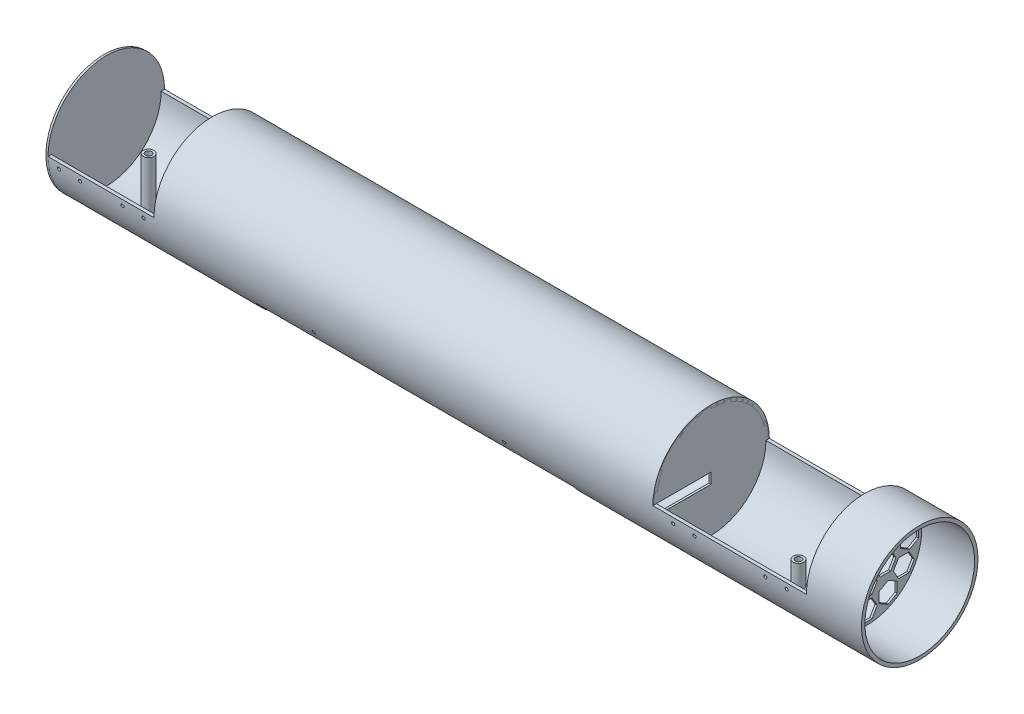
SolidWorks part; units mm, degrees
other "标注1"
sketch "草图27" plane through (-2, 77.9653, 55) normal (0, 1, 0) x (-1, 0, 0)
ref_plane "前视基准面" through (0, 0, 0) normal (0, 0, 1) x (1, 0, 0)
ref_plane "上视基准面" through (0, 0, 0) normal (0, 1, 0) x (1, 0, 0)
ref_plane "右视基准面" through (0, 0, 0) normal (1, 0, 0) x (0, 0, -1)
sketch "草图2" plane through (0, 0, 0) normal (1, 0, 0) x (0, 0, -1)
  circle A0 centre (0, 0) radius 55
  circle A1 centre (0, 0) radius 51.8
  dimension "D1" = 110
  dimension "D2" = 103.6
extrude "凸台-拉伸1" add sketch "草图2" along normal blind 768
ref_plane "基准面4" through (100, 0, 0) normal (1, 0, 0) x (0, 0, -1)
sketch "草图3" plane through (100, 0, 0) normal (1, 0, 0) x (0, 0, -1)
  circle A0 centre (0, 0) radius 54
  dimension "D1" = 108
extrude "凸台-拉伸2" add sketch "草图3" along normal blind 2 separate body
ref_plane "基准面5" through (400, 0, 0) normal (1, 0, 0) x (0, 0, -1)
ref_plane "基准面6" through (565, 0, 0) normal (1, 0, 0) x (0, 0, -1)
sketch "草图7" plane through (0, 0, 0) normal (1, 0, 0) x (0, 0, -1)
  circle A1 centre (0, 0) radius 55
extrude "凸台-拉伸5" add sketch "草图7" against normal blind 2 separate body
ref_plane "基准面7" through (102, 0, 0) normal (1, 0, 0) x (0, 0, -1)
ref_plane "基准面8" through (450, 0, 0) normal (1, 0, 0) x (0, 0, -1)
sketch "草图8" plane through (450, 0, 0) normal (1, 0, 0) x (0, 0, -1)
  circle A0 centre (0, 0) radius 53
ref_plane "基准面9" through (507.5, 0, 0) normal (1, 0, 0) x (0, 0, -1)
ref_plane "基准面10" through (615, 0, 0) normal (1, 0, 0) x (0, 0, -1)
sketch "草图9" plane through (615, 0, 0) normal (1, 0, 0) x (0, 0, -1)
  circle A0 centre (0, 0) radius 53
sketch "草图12" plane through (0, 0, 0) normal (0, 0, 1) x (1, 0, 0)
  line L0 (615, 0) -> (565, 0)
  line L1 (615, -60.5) -> (615, 60.5) construction
  line L2 (768, 0) -> (0, 0) construction
  line L3 (565, -60.5) -> (565, 60.5) construction
sketch "草图14" plane through (0, 0, 0) normal (0, 1, 0) x (1, 0, 0)
  line L1 (571, 55) -> (716, 55)
  line L3 (571, 0) -> (716, 0)
  line L4 (716, 55) -> (716, 0)
  line L5 (768, -55) -> (768, 55) construction
  line L9 (571, 55) -> (571, 0)
  dimension "D1" = 52
  dimension "D3" = 145
ref_plane "基准面11" through (617, 0, 0) normal (1, 0, 0) x (0, 0, -1)
sketch "草图15" plane through (617, 0, 0) normal (1, 0, 0) x (0, 0, -1)
  circle A0 centre (0, 0) radius 53
revolve "切除-旋转1" cut sketch "草图14" angle 180 about L3
sketch "草图16" plane through (0, 0, 0) normal (0, 1, 0) x (1, 0, 0)
  line L0 (100, -60.5) -> (100, 60.5) construction
  line L1 (0, 0) -> (100, 0)
  line L2 (0, 0) -> (0, 55)
  line L3 (0, 55) -> (100, 55)
  line L4 (100, 0) -> (100, 55)
  line L5 (571, 55) -> (0, 55) construction
  dimension "D1" = 100
  dimension "D2" = 55
revolve "切除-旋转2" cut sketch "草图16" angle 180 about L1
ref_plane "基准面12" through (435, 0, 0) normal (1, 0, 0) x (0, 0, -1)
sketch "草图17" plane through (435, 0, 0) normal (1, 0, 0) x (0, 0, -1)
  line L0 (0, 77.9653) -> (0, -80.6413) construction
  circle A0 centre (0, -67) radius 12
  circle A1 centre (0, -67) radius 10
  circle A2 centre (0, 0) radius 55 construction
  dimension "D1" = 24
  dimension "D2" = 20
ref_plane "基准面13" through (200, 0, 0) normal (1, 0, 0) x (0, 0, -1)
ref_plane "基准面14" through (0, 0, -50) normal (0, 0, 1) x (1, 0, 0)
sketch "草图19" plane through (0, 0, -50) normal (0, 0, 1) x (1, 0, 0)
  line L0 (716, 0) -> (571, 0) construction
  line L1 (716, 55) -> (716, 0) construction
  line L2 (571, 0) -> (571, 51.8) construction
  circle A0 centre (693, -5.4) radius 1.5
  circle A1 centre (673, -5.4) radius 1.5
  circle A2 centre (614, -5.4) radius 1.5
  circle A3 centre (594, -5.4) radius 1.5
  dimension "D1" = 3
  dimension "D2" = 3
  dimension "D6" = 3
  dimension "D7" = 3
  dimension "D3" = 20
  dimension "D4" = 5.4
  dimension "D5" = 23
  dimension "D8" = 20
  dimension "D9" = 5.4
  dimension "D10" = 23
  dimension "D11" = 5.4
sketch "草图22" plane through (0, 0, -50) normal (0, 0, 1) x (1, 0, 0)
  line L0 (0, 0) -> (0, -55) construction
  line L1 (100, 55) -> (100, 0) construction
  line L2 (100, 0) -> (0, 0) construction
  circle A0 centre (10, -5.4) radius 1.5
  circle A1 centre (30, -5.4) radius 1.5
  circle A2 centre (70, -5.4) radius 1.5
  circle A3 centre (90, -5.4) radius 1.5
  dimension "D1" = 3
  dimension "D2" = 3
  dimension "D7" = 3
  dimension "D8" = 3
  dimension "D3" = 10
  dimension "D4" = 20
  dimension "D5" = 20
  dimension "D6" = 10
  dimension "D9" = 5.4
extrude "切除-拉伸4" cut sketch "草图22" along normal through all
ref_plane "基准面16" through (597, 0, 0) normal (1, 0, 0) x (0, 0, -1)
sketch "草图23" plane through (597, 0, 0) normal (1, 0, 0) x (0, 0, -1)
  circle A0 centre (0, 0) radius 53
sketch "草图24" plane through (0, 0, -50) normal (0, 0, 1) x (1, 0, 0)
  line L0 (716, 0) -> (571, 0) construction
  line L1 (571, 0) -> (571, 55) construction
  line L2 (716, 55) -> (716, 0) construction
  circle A0 centre (590, -5.4) radius 1.5
  circle A1 centre (610, -5.4) radius 1.5
  circle A2 centre (677, -5.4) radius 1.5
  circle A3 centre (697, -5.4) radius 1.5
  dimension "D3" = 3
  dimension "D4" = 3
  dimension "D6" = 3
  dimension "D7" = 3
  dimension "D1" = 20
  dimension "D2" = 5.4
  dimension "D5" = 20
  dimension "D8" = 5.4
  dimension "D9" = 19
  dimension "D10" = 19
extrude "切除-拉伸5" cut sketch "草图24" along normal through all
ref_plane "基准面17" through (222.4934, 0, 0) normal (1, 0, 0) x (0, 0, -1)
sketch "草图25" plane through (222.4934, 0, 0) normal (1, 0, 0) x (0, 0, -1)
  circle A0 centre (0, -67) radius 12
  circle A1 centre (0, -67) radius 10
  circle A2 centre (0, 0) radius 55 construction
  dimension "D1" = 24
  dimension "D2" = 20
ref_plane "基准面18" through (0, 0, 0) normal (1, 0, 0) x (0, 0, -1)
ref_plane "基准面19" through (470, 0, 0) normal (1, 0, 0) x (0, 0, -1)
ref_plane "基准面20" through (718, 0, 0) normal (1, 0, 0) x (0, 0, -1)
sketch "草图28" plane through (718, 0, 0) normal (1, 0, 0) x (0, 0, -1)
  circle A0 centre (0, 0) radius 54
  dimension "D1" = 108
extrude "凸台-拉伸16" add sketch "草图28" against normal blind 2 separate body
ref_plane "基准面21" through (571, 0, 0) normal (1, 0, 0) x (0, 0, -1)
sketch "草图29" plane through (571, 0, 0) normal (1, 0, 0) x (0, 0, -1)
  circle A0 centre (0, 0) radius 54
  dimension "D1" = 108
extrude "凸台-拉伸17" add sketch "草图29" against normal blind 2 separate body
sketch "草图30" plane through (0, 0, 0) normal (0, 0, 1) x (1, 0, 0)
  line L3 (185.5, 0) -> (485.5, 0)
  line L6 (0, -55) -> (768, -55) construction
  line L7 (185.5, 0) -> (485.5, 0)
  line L8 (185.5, 0) -> (185.5, -55)
  line L9 (185.5, -55) -> (485.5, -55)
  line L10 (485.5, 0) -> (485.5, -55)
  line L11 (571, 0) -> (571, 55) construction
  dimension "D1" = 300
  dimension "D2" = 55
  dimension "D3" = 85.5
sketch "草图31" plane through (571, 0, 0) normal (1, 0, 0) x (0, 0, -1)
  line L0 (-52.8334, 0) -> (0, 0)
  line L1 (0, 0) -> (0, -10)
  line L2 (0, -10) -> (-51.8784, -10)
  arc A0 (-52.8334, 0) -> (-51.8784, -10) centre (0, 0) ccw
  dimension "D1" = 10
extrude "切除-拉伸6" cut sketch "草图31" against normal blind 536
sketch "草图32" plane through (0, 0, 0) normal (0, 0, 1) x (1, 0, 0)
  line L0 (0, -55) -> (768, -55) construction
  line L1 (185.5, 0) -> (485.5, 0)
  line L2 (185.5, 0) -> (185.5, -55)
  line L3 (185.5, -55) -> (485.5, -55)
  line L4 (485.5, 0) -> (485.5, -55)
  line L5 (100, 55) -> (100, 0) construction
  dimension "D1" = 300
  dimension "D2" = 55
  dimension "D3" = 85.5
revolve "切除-旋转4" cut sketch "草图32" angle 54 about axis through (768, 0, 0) along (-1, 0, 0) other way angle 54
sketch "草图35" plane through (718, 0, 0) normal (1, 0, 0) x (0, 0, -1)
  line L0 (0, 0) -> (-43.6869, -31.7404)
  line L1 (0, 0) -> (43.6869, -31.7404)
  line L2 (0, 0) -> (0, -54) construction
  circle A0 centre (0, 0) radius 54 construction
  arc A1 (-43.6869, -31.7404) -> (43.6869, -31.7404) centre (0, 0) ccw
  dimension "D1" = 108
ref_plane "基准面22" through (0, 0, 45) normal (0, 0, 1) x (1, 0, 0)
sketch "草图36" plane through (0, 0, 45) normal (0, 0, 1) x (1, 0, 0)
  line L0 (185.5, -32.3282) -> (485.5, -32.3282) construction
  line L1 (485.5, -32.3282) -> (485.5, -55) construction
  line L2 (185.5, -55) -> (185.5, -32.3282) construction
  circle A0 centre (425.5, -23.4722) radius 1.5
  circle A1 centre (245.5, -23.4722) radius 1.5
  dimension "D3" = 3
  dimension "D5" = 3
  dimension "D1" = 8.856
  dimension "D2" = 60
  dimension "D4" = 60
extrude "切除-拉伸7" cut sketch "草图36" against normal through all both and the other way through all
sketch "草图37" plane through (0, 0, 0) normal (0, 1, 0) x (1, 0, 0)
  line L1 (0, -55) -> (0, 55) construction
  circle A0 centre (40, 0) radius 5
  circle A1 centre (40, 0) radius 3
  dimension "D1" = 10
  dimension "D2" = 6
  dimension "D3" = 40
extrude "凸台-拉伸19" add sketch "草图37" against normal up to body
sketch "草图39" plane through (0, 0, 0) normal (0, 1, 0) x (1, 0, 0)
  line L1 (716, 51.8) -> (716, -51.8) construction
  line L2 (716, 55) -> (716, -55) construction
  circle A0 centre (653.5, 0) radius 5
  circle A1 centre (653.5, 0) radius 3
  point P9 (716, 0)
  dimension "D1" = 10
  dimension "D2" = 6
  dimension "D3" = 62.5
extrude "凸台-拉伸21" add sketch "草图39" against normal up to body
sketch "草图40" plane through (0, 0, 0) normal (0, 1, 0) x (1, 0, 0)
  circle A0 centre (40, 0) radius 3 construction
  circle A1 centre (40, 0) radius 5
  circle A2 centre (40, 0) radius 5
  circle A3 centre (40, 0) radius 3
  dimension "D1" = 0
extrude "切除-拉伸8" cut sketch "草图40" against normal blind 5
sketch "草图41" plane through (0, 0, 0) normal (0, 1, 0) x (1, 0, 0)
  circle A1 centre (653.5, 0) radius 3 construction
  circle A2 centre (653.5, 0) radius 5
  circle A3 centre (653.5, 0) radius 5
  circle A4 centre (653.5, 0) radius 3
  dimension "D1" = 0
extrude "切除-拉伸9" cut sketch "草图41" against normal blind 30
ref_plane "基准面23" through (0, 0, -52.0375) normal (0, 0, 1) x (1, 0, 0)
sketch "草图42" plane through (0, 0, -52.0375) normal (0, 0, 1) x (1, 0, 0)
  line L0 (716, 0) -> (571, 0) construction
  line L1 (716, 55) -> (716, 0) construction
  circle A0 centre (711, -5) radius 1.5
  dimension "D1" = 3
  dimension "D2" = 5
  dimension "D3" = 5
extrude "切除-拉伸10" cut sketch "草图42" against normal blind 44
sketch "草图44" plane through (718, 0, 0) normal (1, 0, 0) x (0, 0, -1)
  line L0 (0, 40.3627) -> (0, 0) construction
  line L1 (4.9412, 48.8975) -> (-4.9208, 48.9093)
  line L2 (-4.9208, 48.9093) -> (-9.8619, 40.3745)
  line L3 (-9.8619, 40.3745) -> (-4.9412, 31.8279)
  line L4 (-4.9412, 31.8279) -> (4.9208, 31.8161)
  line L5 (4.9208, 31.8161) -> (9.8619, 40.3509)
  line L6 (9.8619, 40.3509) -> (4.9412, 48.8975)
  line L7 (4.9412, 28.8975) -> (-4.9208, 28.9093)
  line L8 (-4.9208, 28.9093) -> (-9.8619, 20.3745)
  line L9 (-9.8619, 20.3745) -> (-4.9412, 11.8279)
  line L10 (-4.9412, 11.8279) -> (4.9208, 11.8161)
  line L11 (4.9208, 11.8161) -> (9.8619, 20.3509)
  line L12 (9.8619, 20.3509) -> (4.9412, 28.8975)
  line L13 (4.9412, 8.8975) -> (-4.9208, 8.9093)
  line L14 (-4.9208, 8.9093) -> (-9.8619, 0.3745)
  line L15 (-9.8619, 0.3745) -> (-4.9412, -8.1721)
  line L16 (-4.9412, -8.1721) -> (4.9208, -8.1839)
  line L17 (4.9208, -8.1839) -> (9.8619, 0.3509)
  line L18 (9.8619, 0.3509) -> (4.9412, 8.8975)
  line L31 (28.728, 39.8759) -> (20.1932, 44.8171)
  line L32 (20.1932, 44.8171) -> (11.6466, 39.8963)
  line L33 (11.6466, 39.8963) -> (11.6348, 30.0344)
  line L34 (11.6348, 30.0344) -> (20.1696, 25.0932)
  line L35 (20.1696, 25.0932) -> (28.7162, 30.0139)
  line L36 (28.7162, 30.0139) -> (28.728, 39.8759)
  line L37 (44.8171, 20.1696) -> (39.8963, 28.7162)
  line L38 (39.8963, 28.7162) -> (30.0344, 28.728)
  line L39 (30.0344, 28.728) -> (25.0932, 20.1932)
  line L40 (25.0932, 20.1932) -> (30.0139, 11.6466)
  line L41 (30.0139, 11.6466) -> (39.8759, 11.6348)
  line L42 (39.8759, 11.6348) -> (44.8171, 20.1696)
  line L43 (48.8975, -4.9412) -> (48.9093, 4.9208)
  line L44 (48.9093, 4.9208) -> (40.3745, 9.8619)
  line L45 (40.3745, 9.8619) -> (31.8279, 4.9412)
  line L46 (31.8279, 4.9412) -> (31.8161, -4.9208)
  line L47 (31.8161, -4.9208) -> (40.3509, -9.8619)
  line L48 (40.3509, -9.8619) -> (48.8975, -4.9412)
  line L49 (39.8759, -28.728) -> (44.8171, -20.1932)
  line L50 (44.8171, -20.1932) -> (39.8963, -11.6466)
  line L51 (39.8963, -11.6466) -> (30.0344, -11.6348)
  line L52 (30.0344, -11.6348) -> (25.0932, -20.1696)
  line L53 (25.0932, -20.1696) -> (30.0139, -28.7162)
  line L54 (30.0139, -28.7162) -> (39.8759, -28.728)
  line L55 (20.1696, -44.8171) -> (28.7162, -39.8963)
  line L56 (28.7162, -39.8963) -> (28.728, -30.0344)
  line L57 (28.728, -30.0344) -> (20.1932, -25.0932)
  line L58 (20.1932, -25.0932) -> (11.6466, -30.0139)
  line L59 (11.6466, -30.0139) -> (11.6348, -39.8759)
  line L60 (11.6348, -39.8759) -> (20.1696, -44.8171)
  line L61 (-4.9412, -48.8975) -> (4.9208, -48.9093)
  line L62 (4.9208, -48.9093) -> (9.8619, -40.3745)
  line L63 (9.8619, -40.3745) -> (4.9412, -31.8279)
  line L64 (4.9412, -31.8279) -> (-4.9208, -31.8161)
  line L65 (-4.9208, -31.8161) -> (-9.8619, -40.3509)
  line L66 (-9.8619, -40.3509) -> (-4.9412, -48.8975)
  line L67 (-28.728, -39.8759) -> (-20.1932, -44.8171)
  line L68 (-20.1932, -44.8171) -> (-11.6466, -39.8963)
  line L69 (-11.6466, -39.8963) -> (-11.6348, -30.0344)
  line L70 (-11.6348, -30.0344) -> (-20.1696, -25.0932)
  line L71 (-20.1696, -25.0932) -> (-28.7162, -30.0139)
  line L72 (-28.7162, -30.0139) -> (-28.728, -39.8759)
  line L73 (-44.8171, -20.1696) -> (-39.8963, -28.7162)
  line L74 (-39.8963, -28.7162) -> (-30.0344, -28.728)
  line L75 (-30.0344, -28.728) -> (-25.0932, -20.1932)
  line L76 (-25.0932, -20.1932) -> (-30.0139, -11.6466)
  line L77 (-30.0139, -11.6466) -> (-39.8759, -11.6348)
  line L78 (-39.8759, -11.6348) -> (-44.8171, -20.1696)
  line L79 (-48.8975, 4.9412) -> (-48.9093, -4.9208)
  line L80 (-48.9093, -4.9208) -> (-40.3745, -9.8619)
  line L81 (-40.3745, -9.8619) -> (-31.8279, -4.9412)
  line L82 (-31.8279, -4.9412) -> (-31.8161, 4.9208)
  line L83 (-31.8161, 4.9208) -> (-40.3509, 9.8619)
  line L84 (-40.3509, 9.8619) -> (-48.8975, 4.9412)
  line L85 (-39.8759, 28.728) -> (-44.8171, 20.1932)
  line L86 (-44.8171, 20.1932) -> (-39.8963, 11.6466)
  line L87 (-39.8963, 11.6466) -> (-30.0344, 11.6348)
  line L88 (-30.0344, 11.6348) -> (-25.0932, 20.1696)
  line L89 (-25.0932, 20.1696) -> (-30.0139, 28.7162)
  line L90 (-30.0139, 28.7162) -> (-39.8759, 28.728)
  line L91 (-20.1696, 44.8171) -> (-28.7162, 39.8963)
  line L92 (-28.7162, 39.8963) -> (-28.728, 30.0344)
  line L93 (-28.728, 30.0344) -> (-20.1932, 25.0932)
  line L94 (-20.1932, 25.0932) -> (-11.6466, 30.0139)
  line L95 (-11.6466, 30.0139) -> (-11.6348, 39.8759)
  line L96 (-11.6348, 39.8759) -> (-20.1696, 44.8171)
  line L97 (27.4966, 10.1696) -> (22.5758, 18.7162)
  line L98 (22.5758, 18.7162) -> (12.7139, 18.728)
  line L99 (12.7139, 18.728) -> (7.7727, 10.1932)
  line L100 (7.7727, 10.1932) -> (12.6934, 1.6466)
  line L101 (12.6934, 1.6466) -> (22.5554, 1.6348)
  line L102 (22.5554, 1.6348) -> (27.4966, 10.1696)
  line L103 (22.5554, -18.728) -> (27.4966, -10.1932)
  line L104 (27.4966, -10.1932) -> (22.5758, -1.6466)
  line L105 (22.5758, -1.6466) -> (12.7139, -1.6348)
  line L106 (12.7139, -1.6348) -> (7.7727, -10.1696)
  line L107 (7.7727, -10.1696) -> (12.6934, -18.7162)
  line L108 (12.6934, -18.7162) -> (22.5554, -18.728)
  line L109 (-4.9412, -28.8975) -> (4.9208, -28.9093)
  line L110 (4.9208, -28.9093) -> (9.8619, -20.3745)
  line L111 (9.8619, -20.3745) -> (4.9412, -11.8279)
  line L112 (4.9412, -11.8279) -> (-4.9208, -11.8161)
  line L113 (-4.9208, -11.8161) -> (-9.8619, -20.3509)
  line L114 (-9.8619, -20.3509) -> (-4.9412, -28.8975)
  line L115 (-27.4966, -10.1696) -> (-22.5758, -18.7162)
  line L116 (-22.5758, -18.7162) -> (-12.7139, -18.728)
  line L117 (-12.7139, -18.728) -> (-7.7727, -10.1932)
  line L118 (-7.7727, -10.1932) -> (-12.6934, -1.6466)
  line L119 (-12.6934, -1.6466) -> (-22.5554, -1.6348)
  line L120 (-22.5554, -1.6348) -> (-27.4966, -10.1696)
  line L121 (-22.5554, 18.728) -> (-27.4966, 10.1932)
  line L122 (-27.4966, 10.1932) -> (-22.5758, 1.6466)
  line L123 (-22.5758, 1.6466) -> (-12.7139, 1.6348)
  line L124 (-12.7139, 1.6348) -> (-7.7727, 10.1696)
  line L125 (-7.7727, 10.1696) -> (-12.6934, 18.7162)
  line L126 (-12.6934, 18.7162) -> (-22.5554, 18.728)
  line L127 (4.9412, -11.1025) -> (-4.9208, -11.0907) [skipped]
  line L128 (-4.9208, -11.0907) -> (-9.8619, -19.6255) [skipped]
  line L129 (-9.8619, -19.6255) -> (-4.9412, -28.1721) [skipped]
  line L130 (-4.9412, -28.1721) -> (4.9208, -28.1839) [skipped]
  line L131 (4.9208, -28.1839) -> (9.8619, -19.6491) [skipped]
  line L132 (9.8619, -19.6491) -> (4.9412, -11.1025) [skipped]
  line L133 (4.9412, -31.1025) -> (-4.9208, -31.0907) [skipped]
  line L134 (-4.9208, -31.0907) -> (-9.8619, -39.6255) [skipped]
  line L135 (-9.8619, -39.6255) -> (-4.9412, -48.1721) [skipped]
  line L136 (-4.9412, -48.1721) -> (4.9208, -48.1839) [skipped]
  line L137 (4.9208, -48.1839) -> (9.8619, -39.6491) [skipped]
  line L138 (9.8619, -39.6491) -> (4.9412, -31.1025) [skipped]
  circle A0 centre (0, 40.3627) radius 8.5407 construction
  point P102 (0, 0)
  point P133 (0, 0)
  dimension "D1" = 5
  dimension "D2" = 12
  dimension "D3" = 6
extrude "切除-拉伸12" cut sketch "草图44" against normal blind 10
